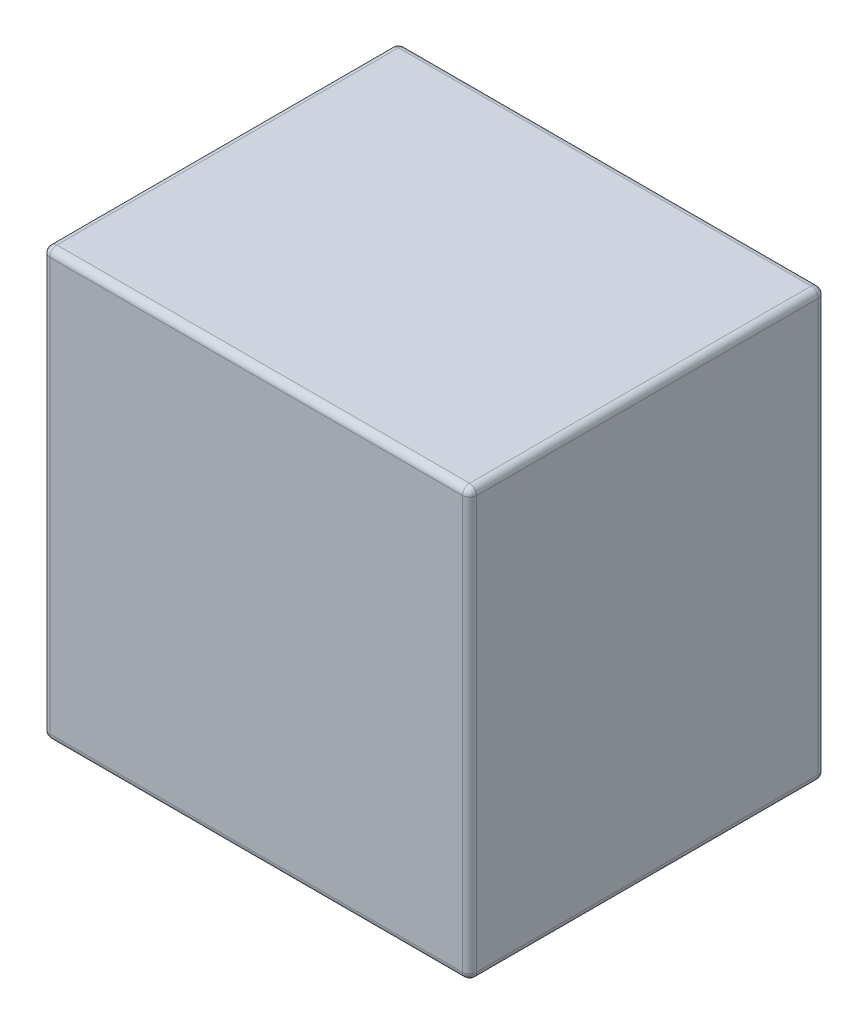
SolidWorks part; units mm, degrees
ref_plane "Front Plane" through (0, 0, 0) normal (1, 0, 0) x (0, 1, 0)
ref_plane "Top Plane" through (0, 0, 0) normal (0, 0, 1) x (0, 1, 0)
ref_plane "Right Plane" through (0, 0, 0) normal (0, 1, 0) x (-1, 0, 0)
sketch "Sketch1" plane through (0, 0, 0) normal (0, 0, 1) x (0, 1, 0)
  line L1 (-3, -3) -> (3, -3)
  line L2 (-3, -3) -> (-3, 3)
  line L3 (-3, 3) -> (3, 3)
  line L4 (3, -3) -> (3, 3)
  line L5 (-3, -3) -> (3, 3) construction
  line L6 (-3, 3) -> (3, -3) construction
  point P0 (0, 0)
  dimension "D1" = 6
  dimension "D2" = 6
extrude "Boss-Extrude1" add sketch "Sketch1" along normal blind 5
fillet "Fillet1" radius 0.1 12 edges at (-3, 3, 2.5) (-3, -3, 2.5) (3, -3, 2.5) (3, 3, 2.5) (3, 0, 5) (0, -3, 5) (-3, 0, 5) (0, 3, 5) (3, 0, 0) (0, -3, 0) (-3, 0, 0) (0, 3, 0)
